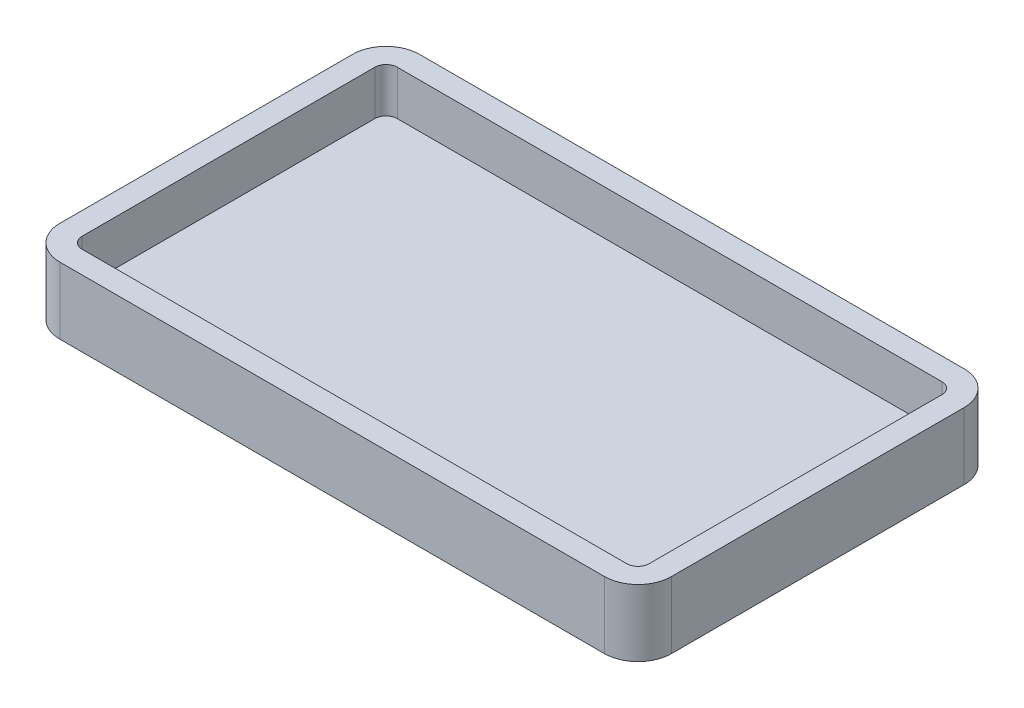
SolidWorks part; units mm, degrees
ref_plane "Front Plane" through (0, 0, 0) normal (0, 0, 1) x (1, 0, 0)
ref_plane "Top Plane" through (0, 0, 0) normal (0, 1, 0) x (1, 0, 0)
ref_plane "Right Plane" through (0, 0, 0) normal (1, 0, 0) x (0, 0, -1)
sketch "Sketch1" plane through (0, 0, 0) normal (0, 1, 0) x (1, 0, 0)
  line L1 (4.7752, 0) -> (82.4757, 0)
  line L2 (0, 4.7752) -> (0, 46.5409)
  line L3 (4.7752, 51.3161) -> (82.4757, 51.3161)
  line L4 (87.2509, 4.7752) -> (87.2509, 46.5409)
  arc A0 (4.7752, 51.3161) -> (0, 46.5409) centre (4.7752, 46.5409) ccw
  arc A1 (87.2509, 46.5409) -> (82.4757, 51.3161) centre (82.4757, 46.5409) ccw
  arc A2 (87.2509, 4.7752) -> (82.4757, 0) centre (82.4757, 4.7752) cw
  arc A3 (0, 4.7752) -> (4.7752, 0) centre (4.7752, 4.7752) ccw
  point P13 (0, 0)
  dimension "D1" = 4.7752
extrude "Extrude1" add sketch "Sketch1" against normal blind 9.525
sketch "Sketch2" plane through (0, 0, 0) normal (0, 1, 0) x (1, 0, 0)
  line L0 (3.175, 46.5409) -> (3.175, 4.7752)
  line L1 (4.7752, 3.175) -> (82.4757, 3.175)
  line L2 (84.0759, 4.7752) -> (84.0759, 46.5409)
  line L3 (82.4757, 48.1411) -> (4.7752, 48.1411)
  line L4 (0, 46.5409) -> (0, 4.7752)
  line L5 (4.7752, 0) -> (82.4757, 0)
  line L6 (87.2509, 4.7752) -> (87.2509, 46.5409)
  line L7 (82.4757, 51.3161) -> (4.7752, 51.3161)
  line L12 (4.7752, 0) -> (82.4757, 0) construction
  line L13 (0, 46.5409) -> (0, 4.7752) construction
  line L14 (82.4757, 51.3161) -> (4.7752, 51.3161) construction
  line L15 (87.2509, 4.7752) -> (87.2509, 46.5409) construction
  arc A0 (3.175, 4.7752) -> (4.7752, 3.175) centre (4.7752, 4.7752) ccw
  arc A1 (82.4757, 3.175) -> (84.0759, 4.7752) centre (82.4757, 4.7752) ccw
  arc A2 (84.0759, 46.5409) -> (82.4757, 48.1411) centre (82.4757, 46.5409) ccw
  arc A3 (4.7752, 48.1411) -> (3.175, 46.5409) centre (4.7752, 46.5409) ccw
  arc A4 (4.7752, 51.3161) -> (0, 46.5409) centre (4.7752, 46.5409) ccw
  arc A5 (0, 4.7752) -> (4.7752, 0) centre (4.7752, 4.7752) ccw
  arc A6 (82.4757, 0) -> (87.2509, 4.7752) centre (82.4757, 4.7752) ccw
  arc A7 (87.2509, 46.5409) -> (82.4757, 51.3161) centre (82.4757, 46.5409) ccw
  arc A10 (82.4757, 0) -> (87.2509, 4.7752) centre (82.4757, 4.7752) ccw
  arc A12 (0, 4.7752) -> (4.7752, 0) centre (4.7752, 4.7752) ccw construction
  arc A13 (4.7752, 51.3161) -> (0, 46.5409) centre (4.7752, 46.5409) ccw construction
  arc A14 (87.2509, 46.5409) -> (82.4757, 51.3161) centre (82.4757, 46.5409) ccw construction
  dimension "D1" = 0
extrude "Extrude2" cut sketch "Sketch2" against normal blind 6.35 contours L0 A0 L1 A1 L2 A2 L3 A3
